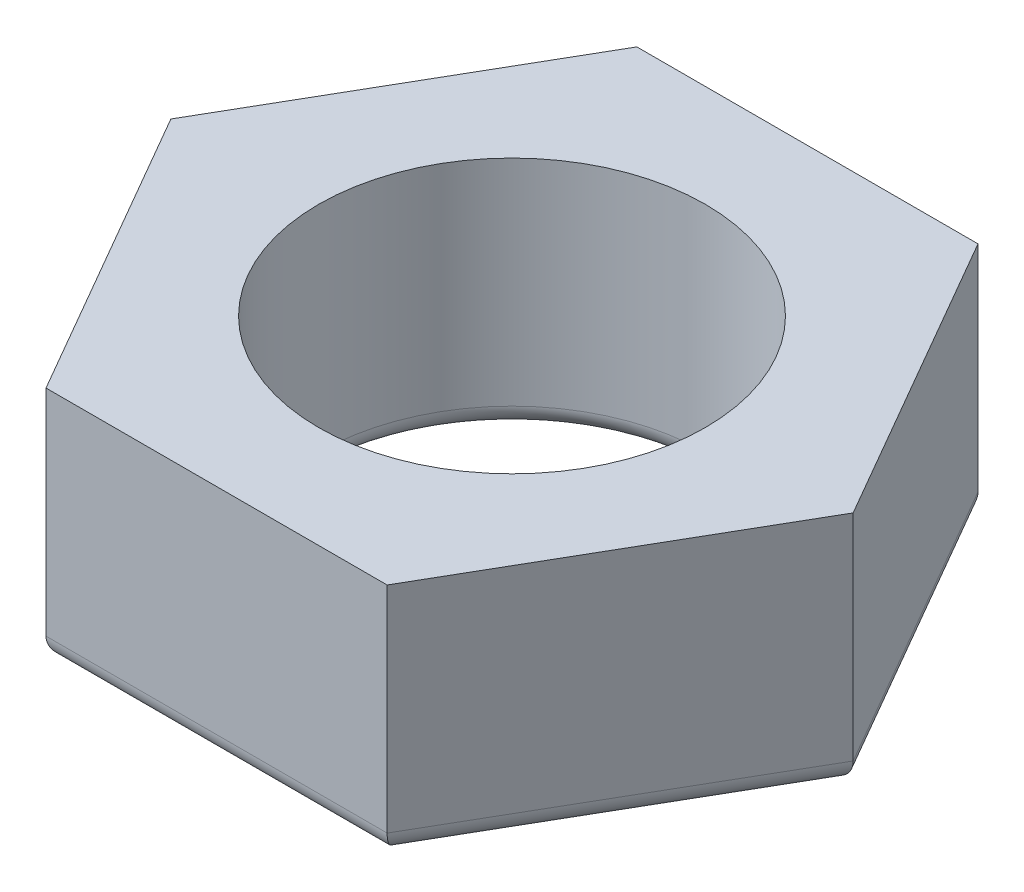
SolidWorks part; units mm, degrees
material "ABS"
ref_plane "Plan de face" through (0, 0, 0) normal (0, 0, 1) x (1, 0, 0)
ref_plane "Plan de dessus" through (0, 0, 0) normal (0, 1, 0) x (1, 0, 0)
ref_plane "Plan de droite" through (0, 0, 0) normal (1, 0, 0) x (0, 0, -1)
sketch "Esquisse1" plane through (0, 0, 0) normal (0, 1, 0) x (1, 0, 0)
  line L1 (1.5877, 2.75) -> (-1.5877, 2.75)
  line L2 (-1.5877, 2.75) -> (-3.1754, 0)
  line L3 (-3.1754, 0) -> (-1.5877, -2.75)
  line L4 (-1.5877, -2.75) -> (1.5877, -2.75)
  line L5 (1.5877, -2.75) -> (3.1754, 0)
  line L6 (3.1754, 0) -> (1.5877, 2.75)
  circle A0 centre (0, 0) radius 2.75 construction
  dimension "D1" = 5.5
extrude "Boss.-Extru.1" add sketch "Esquisse1" along normal blind 2.2
hole_wizard "Dégagement M31" positions "Esquisse2" profile "Esquisse3" hole size "M3" standard "Ansi Metric"
sketch "Esquisse2" plane through (0, 2.2, 0) normal (0, 1, 0) x (1, 0, 0)
  point P0 (0, 0)
sketch "Esquisse3" plane through (0, 2.2, 0) normal (1, 0, 0) x (0, 0, 1)
  line L0 (0, 0) -> (0, 3.2815)
  line L1 (0, 3.2815) -> (1.8, 2.2)
  line L2 (1.8, 2.2) -> (1.8, 0)
  line L5 (1.8, 0) -> (0, 0)
  line L10 (0, 3.2815) -> (-1.8, 2.2) construction
  line L11 (0, -6.35) -> (0, 107.95) construction
  dimension "Diamètre du perçage" = 3.6
  dimension "Profondeur du perçage" = 2.2
  dimension "Angle de pointe" = 118
fillet "Congé1" radius 0.2 7 edges at (0, 0, -2.75) (-2.3816, 0, -1.375) (-2.3816, 0, 1.375) (0, 0, 2.75) (2.3816, 0, 1.375) (2.3816, 0, -1.375) (0, 0, 1.8)
